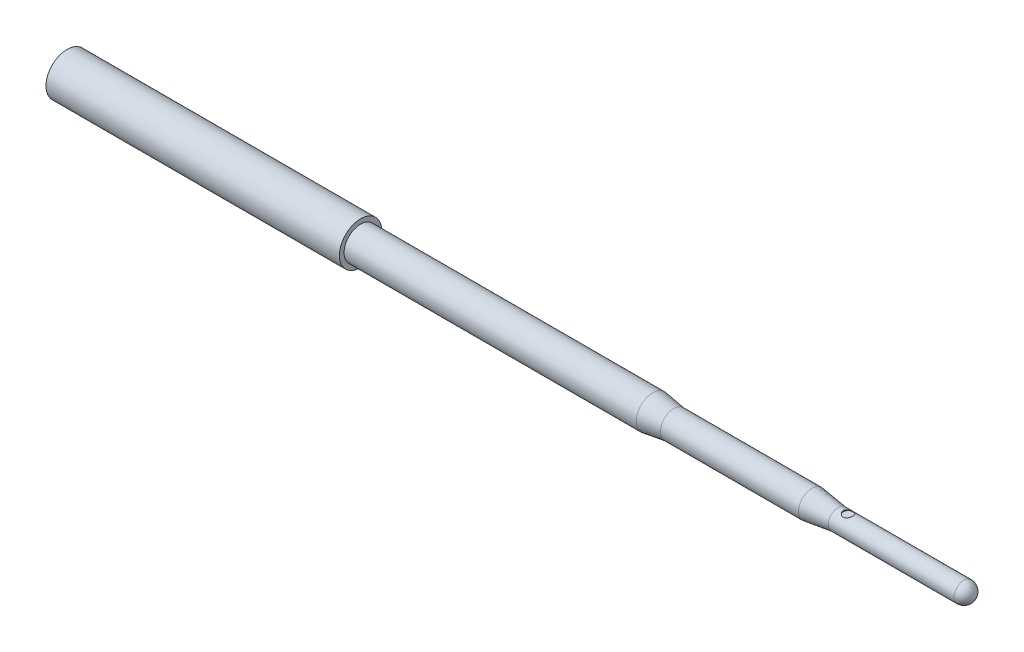
SolidWorks part; units mm, degrees
ref_plane "Front Plane" through (0, 0, 0) normal (0, 0, 1) x (1, 0, 0)
ref_plane "Top Plane" through (0, 0, 0) normal (0, 1, 0) x (1, 0, 0)
ref_plane "Right Plane" through (0, 0, 0) normal (1, 0, 0) x (0, 0, -1)
sketch "Sketch1" plane through (0, 0, 0) normal (0, 1, 0) x (1, 0, 0)
  line L0 (-36.2617, 25.4781) -> (-30.1538, 24.5891)
  line L1 (-120.7929, 25.4781) -> (-36.2617, 25.4781)
  line L2 (17.4019, 23.5604) -> (9.8004, 24.5891)
  line L3 (-120.7929, 25.4781) -> (-120.7929, 26.8243)
  line L4 (53.8001, 20.6902) -> (-205.7051, 20.6902)
  line L5 (-30.1538, 24.5891) -> (9.8004, 24.5891)
  line L6 (-120.7929, 26.8243) -> (-205.7051, 26.8243)
  line L7 (-205.7051, 20.6902) -> (-205.7051, 26.8243)
  line L8 (17.4019, 23.5604) -> (53.8001, 23.5604)
  line L9 (53.8001, 23.5604) -> (53.8001, 20.6902)
  dimension "D1" = 4.7879
  dimension "D2" = 39.9542
  dimension "D3" = 36.3982
  dimension "D4" = 84.5312
  dimension "D5" = 6.1722
  dimension "D6" = 1.3462
  dimension "D7" = 84.9122
  dimension "D8" = 2.8702
  dimension "D9" = 7.6708
  dimension "D10" = 3.8989
revolve "Revolve1" add sketch "Sketch1" angle 360 about L4
sketch "Sketch3" plane through (53.8001, 0, 0) normal (1, 0, 0) x (0, 0, -1)
  circle A0 centre (20.6902, 0) radius 2.8702
extrude "Boss-Extrude1" add sketch "Sketch3" along normal blind 2.8702
fillet "Fillet1" radius 2.8702 1 edges at (56.6703, 0, -23.5604)
sketch "Sketch4" plane through (0, 0, 0) normal (0, 1, 0) x (1, 0, 0)
  line L0 (20.2721, 23.5604) -> (20.2721, 17.82) construction
  line L1 (53.8001, 23.5604) -> (17.4019, 23.5604) construction
  line L2 (17.4019, 17.82) -> (53.8001, 17.82) construction
  line L3 (53.8001, 23.5604) -> (53.8001, 17.82) construction
  circle A0 centre (20.2721, 20.6902) radius 1.397
  dimension "D1" = 2.794
  dimension "D2" = 33.528
extrude "Cut-Extrude1" cut sketch "Sketch4" along normal blind 2.54 from offset 2.54
